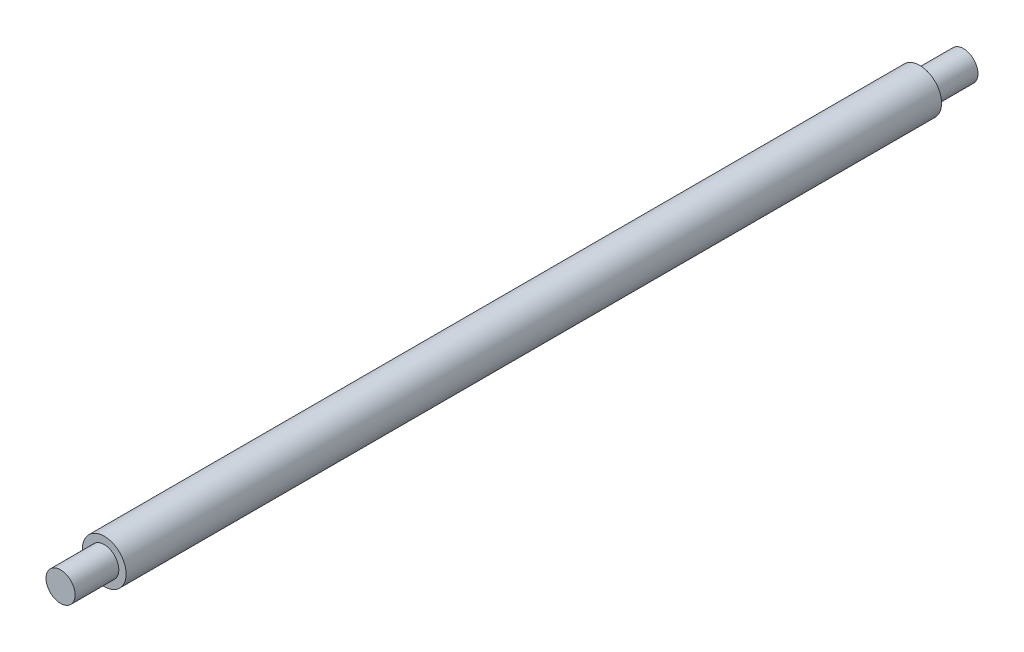
SolidWorks part; units mm, degrees
ref_plane "Front" through (0, 0, 0) normal (0, 0, 1) x (1, 0, 0)
ref_plane "Top" through (0, 0, 0) normal (0, 1, 0) x (1, 0, 0)
ref_plane "Right" through (0, 0, 0) normal (1, 0, 0) x (0, 0, -1)
sketch "Sketch1" plane through (0, 0, 0) normal (0, 0, 1) x (1, 0, 0)
  circle A0 centre (0, 0) radius 9.525
  dimension "D1" = 19.05
extrude "Boss-Extrude1" add sketch "Sketch1" along normal blind 355.6
sketch "Sketch2" plane through (0, 0, 355.6) normal (0, 0, 1) x (1, 0, 0)
  circle A0 centre (0, 0) radius 6.35
  dimension "D1" = 12.7
extrude "Boss-Extrude2" add sketch "Sketch2" along normal blind 19.05
sketch "Sketch3" plane through (0, 0, 0) normal (0, 0, -1) x (-1, 0, 0)
  circle A0 centre (0, 0) radius 6.35
  dimension "D1" = 12.7
extrude "Boss-Extrude3" add sketch "Sketch3" along normal blind 19.05
